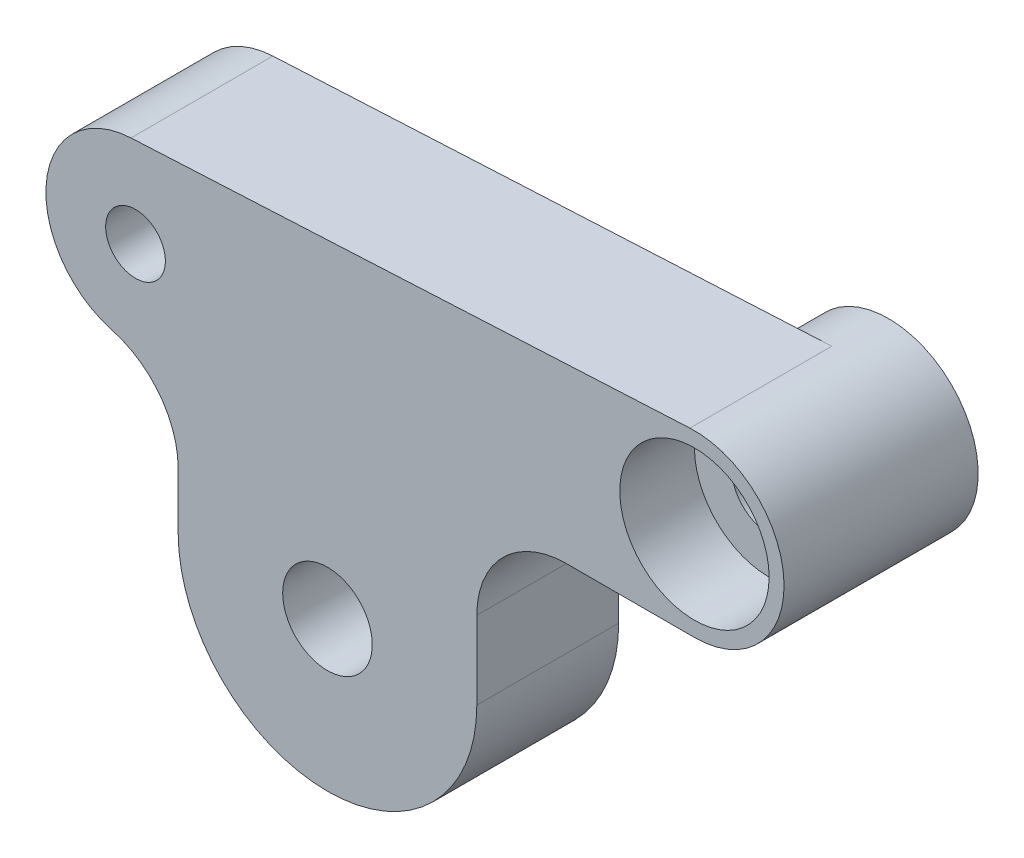
SolidWorks part; units mm, degrees
material "Vero PureWhite"
ref_plane "前视基准面" through (0, 0, 0) normal (0, 0, 1) x (1, 0, 0)
ref_plane "上视基准面" through (0, 0, 0) normal (0, 1, 0) x (1, 0, 0)
ref_plane "右视基准面" through (0, 0, 0) normal (1, 0, 0) x (0, 0, -1)
other "Configuration Table"
sketch "草图1" plane through (0, 0, 0) normal (0, 0, 1) x (1, 0, 0)
  line L0 (0, 0) -> (29.7261, 0) construction
  line L1 (0, 0) -> (24.5746, 17.2073) construction
  line L2 (0, 0) -> (-12.8558, 15.3209) construction
  line L3 (-10, 0) -> (-10, 9.3209)
  line L4 (-10, 9.3209) -> (-12.8558, 9.3209)
  line L5 (10, 0) -> (10, 11.2073)
  line L6 (10, 11.2073) -> (24.5746, 11.2073)
  line L7 (24.2726, 23.1997) -> (-13.1578, 21.3133)
  arc A0 (-10, 0) -> (10, 0) centre (0, 0) ccw
  arc A1 (24.2726, 23.1997) -> (24.5746, 11.2073) centre (24.5746, 17.2073) cw
  arc A2 (-13.1578, 21.3133) -> (-12.8558, 9.3209) centre (-12.8558, 15.3209) ccw
  dimension "D6" = 6
  dimension "D7" = 10
  dimension "D1" = 30
  dimension "D2" = 20
  dimension "D3" = 35
  dimension "D4" = 50
extrude "凸台-拉伸1" add sketch "草图1" along normal blind 9.5
sketch "草图2" plane through (0, 0, 0) normal (0, 0, -1) x (-1, 0, 0)
  circle A0 centre (0, 0) radius 3
  dimension "D1" = 6
extrude "切除-拉伸1" cut sketch "草图2" against normal through all
sketch "草图3" plane through (0, 0, 0) normal (0, 0, -1) x (-1, 0, 0)
  circle A1 centre (-24.5746, 17.2073) radius 6
  arc A2 (-24.2726, 23.1997) -> (-24.5746, 11.2073) centre (-24.5746, 17.2073) ccw construction
extrude "凸台-拉伸2" add sketch "草图3" along normal blind 3.5
sketch "草图4" plane through (0, 0, -3.5) normal (0, 0, -1) x (-1, 0, 0)
  circle A1 centre (-24.5746, 17.2073) radius 2.5
  circle A2 centre (-24.5746, 17.2073) radius 6 construction
extrude "切除-拉伸2" cut sketch "草图4" against normal through all
sketch "草图5" plane through (0, 0, 9.5) normal (0, 0, 1) x (1, 0, 0)
  circle A0 centre (24.5746, 17.2073) radius 5
  arc A1 (24.5746, 11.2073) -> (24.2726, 23.1997) centre (24.5746, 17.2073) ccw construction
extrude "切除-拉伸3" cut sketch "草图5" against normal offset from surface (5 mm away) 8 up to face at (22.0746, 17.2073, -3.5)
sketch "草图6" plane through (0, 0, 0) normal (0, 0, -1) x (-1, 0, 0)
  circle A0 centre (12.8558, 15.3209) radius 2
  dimension "D1" = 4
extrude "切除-拉伸4" cut sketch "草图6" against normal through all
sketch "草图8" plane through (0, 0, 0) normal (0, 0, -1) x (-1, 0, 0)
  circle A0 centre (12.8558, 15.3209) radius 4
  dimension "D1" = 8
extrude "切除-拉伸5" cut sketch "草图8" against normal blind 6
fillet "圆角1" radius 6 2 edges at (-10, 9.3209, 4.75) (10, 11.2073, 4.75)
